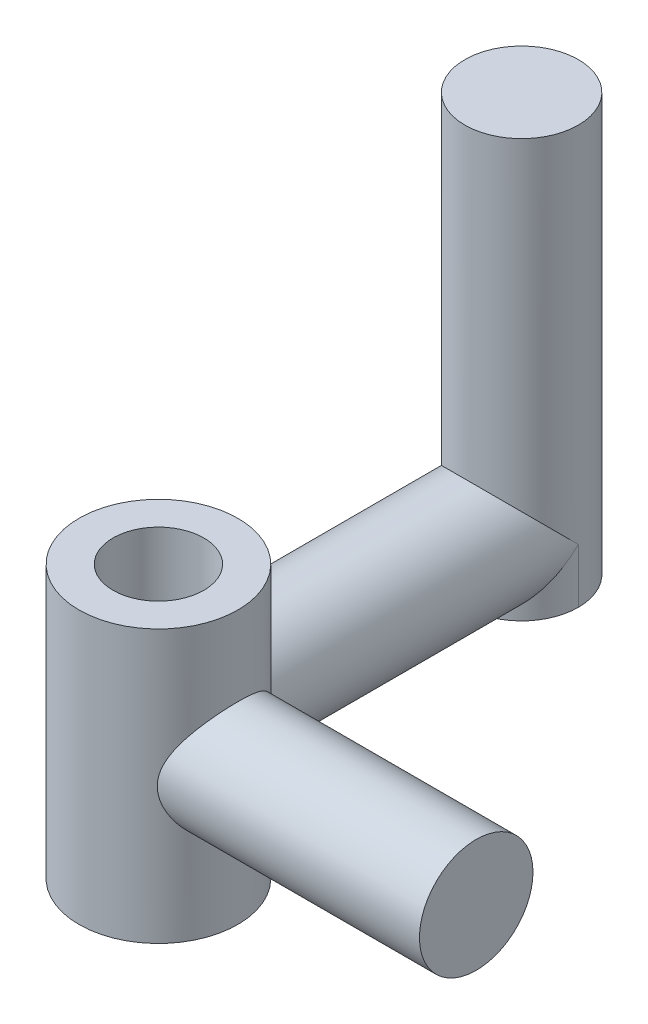
SolidWorks part; units mm, degrees
ref_plane "Front Plane" through (0, 0, 0) normal (0, 0, 1) x (1, 0, 0)
ref_plane "Top Plane" through (0, 0, 0) normal (0, 1, 0) x (1, 0, 0)
ref_plane "Right Plane" through (0, 0, 0) normal (1, 0, 0) x (0, 0, -1)
sketch "Sketch2" plane through (0, 0, 0) normal (0, 1, 0) x (1, 0, 0)
  circle A0 centre (0, 0) radius 1
  circle A1 centre (0, 0) radius 1.75
extrude "Boss-Extrude1" add sketch "Sketch2" along normal mid plane 6
sketch "Sketch3" plane through (0, 0, 0) normal (1, 0, 0) x (0, 0, -1)
  circle A0 centre (0, 0) radius 1.25
extrude "Boss-Extrude2" add sketch "Sketch3" along normal blind 7
sketch "Sketch4" plane through (0, 0, 0) normal (0, 0, 1) x (1, 0, 0)
  circle A0 centre (0, 0) radius 1.25
extrude "Boss-Extrude3" add sketch "Sketch4" against normal blind 8
sketch "Sketch5" plane through (0, 0, 0) normal (0, 1, 0) x (1, 0, 0)
  line L0 (1.25, 8) -> (-1.25, 8) construction
  circle A0 centre (0, 8) radius 1.25
extrude "Boss-Extrude4" add sketch "Sketch5" along normal blind 8
sketch "Sketch6" plane through (0, 0, 0) normal (0, -1, 0) x (1, 0, 0)
  line L0 (1.25, -8) -> (-1.25, -8) construction
  circle A0 centre (0, -8) radius 1.25
extrude "Boss-Extrude5" add sketch "Sketch6" along normal blind 1.2
